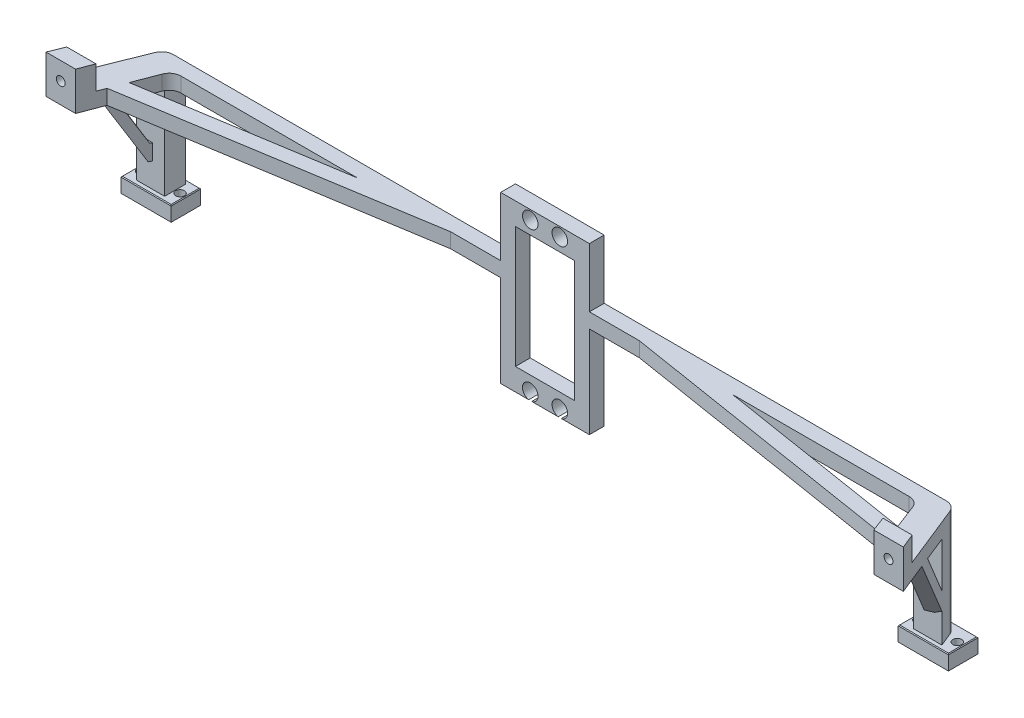
SolidWorks part; units mm, degrees
ref_plane "Plan de face" through (0, 0, 0) normal (0, 0, 1) x (1, 0, 0)
ref_plane "Plan de dessus" through (0, 0, 0) normal (0, 1, 0) x (1, 0, 0)
ref_plane "Plan de droite" through (0, 0, 0) normal (1, 0, 0) x (0, 0, -1)
sketch "Esquisse1" plane through (0, 0, 0) normal (0, 0, 1) x (1, 0, 0)
  line L0 (-10, 20.5) -> (10, 20.5)
  line L1 (-15, 25.5) -> (15, 25.5)
  line L2 (-15, 25.5) -> (-15, -25.5)
  line L3 (-15, -25.5) -> (15, -25.5)
  line L4 (15, 25.5) -> (15, -25.5)
  line L5 (-15, 25.5) -> (15, -25.5) construction
  line L6 (-15, -25.5) -> (15, 25.5) construction
  line L7 (10, 20.5) -> (10, -20.5)
  line L8 (-10, -20.5) -> (10, -20.5)
  line L9 (-10, 20.5) -> (-10, -20.5)
  point P0 (0, 0)
  dimension "D1" = 30
  dimension "D2" = 51
  dimension "D3" = 5
extrude "Boss.-Extru.1" add sketch "Esquisse1" along normal blind 5
ref_plane "Plan1" through (0, -3, 0) normal (0, -1, 0) x (-1, 0, 0)
sketch "Esquisse2" plane through (0, -3, 0) normal (0, -1, 0) x (-1, 0, 0)
  line L0 (-15, 0) -> (-130.7112, 0)
  line L1 (-140, 2.2361) -> (-140, -51.5937) construction
  line L2 (-125.9217, -2.5) -> (74.7377, -2.5) construction
  line L3 (-145, -28.8) -> (-135, -28.8)
  line L4 (-150.5755, -28.8) -> (-133, -28.8) construction
  line L5 (-134.4221, -2.5071) -> (-145, -28.8)
  line L6 (-15, -5) -> (-123.1664, -5)
  line L7 (-126.9037, -7.5744) -> (-135, -28.8)
  line L8 (-15, 0) -> (-15, -5)
  line L9 (0, 30.1998) -> (0, -12.5) construction
  line L10 (15, 0) -> (130.7112, 0)
  line L11 (134.4221, -2.5071) -> (145, -28.8)
  line L12 (145, -28.8) -> (135, -28.8)
  line L13 (126.9037, -7.5744) -> (135, -28.8)
  line L14 (15, -5) -> (123.1664, -5)
  line L15 (15, 0) -> (15, -5)
  arc A0 (-123.1664, -5) -> (-126.9037, -7.5744) centre (-123.1664, -9) ccw
  arc A1 (-130.7112, 0) -> (-134.4221, -2.5071) centre (-130.7112, -4) ccw
  arc A2 (130.7112, 0) -> (134.4221, -2.5071) centre (130.7112, -4) cw
  arc A3 (123.1664, -5) -> (126.9037, -7.5744) centre (123.1664, -9) cw
  point P12 (-140, -28.8)
  dimension "D2" = 4
  dimension "D1" = 10
ref_plane "Plan2" through (0, 8, 0) normal (0, 1, 0) x (1, 0, 0)
sketch "Esquisse3" plane through (0, 8, 0) normal (0, 1, 0) x (1, 0, 0)
  line L6 (130.7112, 0) -> (15, 0)
  line L7 (15, 0) -> (15, -5)
  line L8 (15, -5) -> (123.1664, -5)
  line L9 (126.9037, -7.5744) -> (135, -28.8)
  line L10 (135, -28.8) -> (145, -28.8)
  line L11 (145, -28.8) -> (134.4221, -2.5071)
  line L12 (130.7112, 0) -> (15, 0)
  line L13 (15, 0) -> (15, -5)
  line L14 (15, -5) -> (123.1664, -5)
  line L15 (126.9037, -7.5744) -> (135, -28.8)
  line L16 (135, -28.8) -> (145, -28.8)
  line L17 (145, -28.8) -> (134.4221, -2.5071)
  line L18 (-123.1664, -5) -> (-15, -5)
  line L19 (-135, -28.8) -> (-126.9037, -7.5744)
  line L20 (-145, -28.8) -> (-135, -28.8)
  line L21 (-134.4221, -2.5071) -> (-145, -28.8)
  line L22 (-15, 0) -> (-130.7112, 0)
  line L23 (-15, -5) -> (-15, 0)
  line L24 (-123.1664, -5) -> (-15, -5)
  line L25 (-135, -28.8) -> (-126.9037, -7.5744)
  line L26 (-145, -28.8) -> (-135, -28.8)
  line L27 (-134.4221, -2.5071) -> (-145, -28.8)
  line L28 (-15, 0) -> (-130.7112, 0)
  line L29 (-15, -5) -> (-15, 0)
  arc A2 (126.9037, -7.5744) -> (123.1664, -5) centre (123.1664, -9) ccw
  arc A3 (134.4221, -2.5071) -> (130.7112, 0) centre (130.7112, -4) ccw
  arc A4 (126.9037, -7.5744) -> (123.1664, -5) centre (123.1664, -9) ccw
  arc A5 (134.4221, -2.5071) -> (130.7112, 0) centre (130.7112, -4) ccw
  arc A6 (-123.1664, -5) -> (-126.9037, -7.5744) centre (-123.1664, -9) ccw
  arc A7 (-130.7112, 0) -> (-134.4221, -2.5071) centre (-130.7112, -4) ccw
  arc A8 (-123.1664, -5) -> (-126.9037, -7.5744) centre (-123.1664, -9) ccw
  arc A9 (-130.7112, 0) -> (-134.4221, -2.5071) centre (-130.7112, -4) ccw
  dimension "D1" = 0
  dimension "D2" = 0
extrude "Boss.-Extru.3" add sketch "Esquisse3" against normal blind 5
sketch "Esquisse4" plane through (0, 8, 0) normal (0, 1, 0) x (-1, 0, 0)
  line L0 (145, 28.8) -> (135, 28.8) construction
  line L1 (145, 28.8) -> (135, 28.8)
  line L2 (134.4221, 2.5071) -> (145, 28.8) construction
  line L3 (142.9885, 23.8) -> (145, 28.8)
  line L4 (135, 28.8) -> (126.9037, 7.5744) construction
  line L5 (135, 28.8) -> (133.0928, 23.8)
  line L6 (142.9885, 23.8) -> (133.0928, 23.8)
  line L7 (0, 89.6552) -> (0, -79.8852) construction
  line L8 (-142.9885, 23.8) -> (-145, 28.8)
  line L9 (-142.9885, 23.8) -> (-133.0928, 23.8)
  line L10 (-135, 28.8) -> (-133.0928, 23.8)
  line L11 (-145, 28.8) -> (-135, 28.8)
  dimension "D1" = 5
extrude "Boss.-Extru.4" add sketch "Esquisse4" along normal blind 8
sketch "Esquisse5" plane through (0, 25.5, 0) normal (0, 1, 0) x (1, 0, 0)
  line L4 (15, 0) -> (-15, 0)
  line L5 (-15, 0) -> (-15, -5)
  line L6 (-15, -5) -> (15, -5)
  line L7 (15, -5) -> (15, 0)
  line L8 (15, 0) -> (-15, 0)
  line L9 (-15, 0) -> (-15, -5)
  line L10 (-15, -5) -> (15, -5)
  line L11 (15, -5) -> (15, 0)
  dimension "D1" = 0
extrude "Boss.-Extru.5" add sketch "Esquisse5" along normal blind 2.5
sketch "Esquisse6" plane through (0, -25.5, 0) normal (0, -1, 0) x (1, 0, 0)
  line L4 (-15, 0) -> (15, 0)
  line L5 (15, 0) -> (15, 5)
  line L6 (15, 5) -> (-15, 5)
  line L7 (-15, 5) -> (-15, 0)
  line L8 (-15, 0) -> (15, 0)
  line L9 (15, 0) -> (15, 5)
  line L10 (15, 5) -> (-15, 5)
  line L11 (-15, 5) -> (-15, 0)
  dimension "D1" = 0
extrude "Boss.-Extru.6" add sketch "Esquisse6" along normal blind 2.5
sketch "Esquisse7" plane through (0, 0, 23.8) normal (0, 0, -1) x (-1, 0, 0)
  line L0 (0, 0) -> (0, 76.3627) construction
  circle A0 centre (-140, 10) radius 1.5
  circle A1 centre (140, 10) radius 1.5
extrude "Enlèv. mat.-Extru.1" cut sketch "Esquisse7" against normal through all
sketch "Esquisse8" plane through (0, 0, 5) normal (0, 0, 1) x (1, 0, 0)
  circle A0 centre (-5, 24.925) radius 2.625
  circle A1 centre (5, 24.925) radius 2.625
  circle A2 centre (-5, -25.425) radius 2.625
  circle A3 centre (5, -25.425) radius 2.625
extrude "Enlèv. mat.-Extru.2" cut sketch "Esquisse8" against normal through all
sketch "Esquisse10" plane through (15, 0, 0) normal (1, 0, 0) x (0, 0, -1)
  line L1 (-2.5, 33.5364) -> (-2.5, -60.476) construction
  line L2 (-5.5, -23) -> (0.5, -23)
  line L3 (-7.5, -25) -> (-7.5, -26)
  line L4 (0, -28) -> (0, 3)
  line L5 (0, 3) -> (-5, 3)
  line L6 (-5, 3) -> (-5, -28)
  line L7 (-5, -28) -> (0, -28)
  line L9 (0, 3) -> (-5, 3)
  line L12 (-5.5, -28) -> (0.5, -28)
  line L13 (2.5, -25) -> (2.5, -26)
  line L14 (-7.5, -23) -> (2.5, -28) construction
  line L15 (-7.5, -28) -> (2.5, -23) construction
  line L16 (-5, 28) -> (0, 28) construction
  line L17 (-5, 28) -> (0, 28)
  line L18 (0, -28) -> (-5, -28) construction
  arc A0 (0.5, -28) -> (2.5, -26) centre (0.5, -26) ccw
  arc A1 (0.5, -23) -> (2.5, -25) centre (0.5, -25) cw
  arc A2 (-7.5, -26) -> (-5.5, -28) centre (-5.5, -26) ccw
  arc A3 (-5.5, -23) -> (-7.5, -25) centre (-5.5, -25) ccw
  point P2 (-2.5, -25.5)
  point P11 (-2.5, -28)
  point P14 (-2.5, 28)
  dimension "D4" = 2
  dimension "D2" = 10
  dimension "D3" = 5
  dimension "D1" = 0
sketch "Esquisse12" plane through (0, 8, 0) normal (0, 1, 0) x (1, 0, 0)
  line L0 (-129.9983, -15.6872) -> (-63.4333, -5)
  line L1 (-133.0928, -23.8) -> (-126.9037, -7.5744) construction
  line L2 (-123.1664, -5) -> (-15, -5) construction
  line L3 (-132.0559, -21.0816) -> (-31.8922, -5)
  line L4 (-132.0559, -21.0816) -> (-129.9983, -15.6872)
  line L5 (-63.4333, -5) -> (-31.8922, -5)
  line L6 (0, 40.2666) -> (0, -55.5765) construction
  line L7 (132.0559, -21.0816) -> (129.9983, -15.6872)
  line L8 (132.0559, -21.0816) -> (31.8922, -5)
  line L9 (63.4333, -5) -> (31.8922, -5)
  line L10 (129.9983, -15.6872) -> (63.4333, -5)
  dimension "D1" = 60
  dimension "D2" = 5
extrude "Boss.-Extru.8" add sketch "Esquisse12" against normal blind 5
sketch "Esquisse13" plane through (0, 3, 0) normal (0, -1, 0) x (1, 0, 0)
  line L0 (-136.2297, 7) -> (-126.6846, 7)
  line L1 (-129.9983, 15.6872) -> (-126.9037, 7.5744) construction
  line L2 (-126.6846, 7) -> (-126.6846, 0)
  line L3 (0, 48.0822) -> (0, -50.1932) construction
  line L4 (136.2297, 7) -> (126.6846, 7)
  line L5 (126.6846, 7) -> (126.6846, 0)
  line L6 (130.7112, 0) -> (126.6846, 0)
  line L7 (-31.8922, 5) -> (-132.0559, 21.0816)
  line L8 (-132.0559, 21.0816) -> (-135, 28.8)
  line L9 (-135, 28.8) -> (-145, 28.8)
  line L10 (-145, 28.8) -> (-134.4221, 2.5071)
  line L11 (-130.7112, 0) -> (-15, 0)
  line L12 (-15, 0) -> (-15, 5)
  line L13 (-15, 5) -> (-31.8922, 5)
  line L14 (-31.8922, 5) -> (-132.0559, 21.0816)
  line L15 (-132.0559, 21.0816) -> (-135, 28.8)
  line L16 (-135, 28.8) -> (-145, 28.8)
  line L17 (-136.2297, 7) -> (-134.4221, 2.5071)
  line L18 (-130.7112, 0) -> (-126.6846, 0)
  line L19 (-15, 0) -> (-15, 5)
  line L20 (-15, 5) -> (-31.8922, 5)
  line L21 (132.0559, 21.0816) -> (31.8922, 5)
  line L22 (31.8922, 5) -> (15, 5)
  line L23 (15, 5) -> (15, 0)
  line L24 (15, 0) -> (130.7112, 0)
  line L25 (134.4221, 2.5071) -> (145, 28.8)
  line L26 (145, 28.8) -> (135, 28.8)
  line L27 (135, 28.8) -> (132.0559, 21.0816)
  line L29 (31.8922, 5) -> (15, 5)
  line L30 (15, 5) -> (15, 0)
  line L31 (126.6846, 0) -> (130.7112, 0)
  line L32 (134.4221, 2.5071) -> (136.2297, 7)
  line L34 (135, 28.8) -> (132.0559, 21.0816)
  line L35 (136.2297, 7) -> (134.4221, 2.5071)
  arc A0 (134.4221, 2.5071) -> (130.7112, 0) centre (130.7112, 4) cw
  arc A1 (-134.4221, 2.5071) -> (-130.7112, 0) centre (-130.7112, 4) ccw
  arc A2 (-134.4221, 2.5071) -> (-130.7112, 0) centre (-130.7112, 4) ccw
  arc A3 (130.7112, 0) -> (134.4221, 2.5071) centre (130.7112, 4) ccw
  arc A4 (130.7112, 0) -> (134.4221, 2.5071) centre (130.7112, 4) ccw
  line M20 (-145, 28.8) -> (-134.4221, 2.5071)
  arc M21 (-134.4221, 2.5071) -> (-130.7112, 0) centre (-130.7112, 4) ccw
  line M22 (-130.7112, 0) -> (-15, 0)
  dimension "D3" = 7
  dimension "D1" = 0
  dimension "D2" = 0
extrude "Boss.-Extru.9" add sketch "Esquisse13" along normal through all contours L2 L0 M20 M21 M22 | A0 L32 L4 L5 L6
sketch "Esquisse15" plane through (-114.8284, 0, -46.1964) normal (-0.9277, 0, -0.3732) x (-0.3732, 0, 0.9277)
  line L0 (56.0426, -14.3205) -> (66.0426, 3)
  line L1 (56.4099, -19.6843) -> (69.5067, 3)
  line L2 (56.0426, -14.3205) -> (56.4099, -19.6843)
  line L8 (75.4485, 8) -> (52.497, 8)
  line L9 (52.497, 8) -> (52.497, -28)
  line L10 (52.497, -28) -> (57.3399, -28)
  line L11 (57.3399, -28) -> (57.3399, 3)
  line L12 (57.3399, 3) -> (80.838, 3)
  line L13 (80.838, 3) -> (80.838, 16)
  line L14 (80.838, 16) -> (75.4485, 16)
  line L15 (75.4485, 16) -> (75.4485, 8)
  line L20 (66.0426, 3) -> (69.5067, 3)
  dimension "D2" = 60
  dimension "D3" = 20
  dimension "D4" = 3
  dimension "D1" = 0
extrude "Boss.-Extru.11" add sketch "Esquisse15" against normal blind 5
mirror "Symétrie3" about plane through (0, 0, 0) normal (1, 0, 0) of "Boss.-Extru.11"
sketch "Esquisse16" plane through (0, -28, 0) normal (0, -1, 0) x (1, 0, 0)
  line L0 (136.2297, 7) -> (126.6846, 7) construction
  line L1 (122.9572, 8.5) -> (139.9572, 8.5)
  line L2 (122.9572, 8.5) -> (122.9572, -1.5)
  line L3 (122.9572, -1.5) -> (139.9572, -1.5)
  line L4 (139.9572, 8.5) -> (139.9572, -1.5)
  line L5 (122.9572, 8.5) -> (139.9572, -1.5) construction
  line L6 (122.9572, -1.5) -> (139.9572, 8.5) construction
  line L7 (126.6846, 7) -> (126.6846, 0) construction
  line L8 (0, 67.4594) -> (0, -56.7864) construction
  line L9 (-122.9572, -1.5) -> (-139.9572, -1.5)
  line L10 (-139.9572, 8.5) -> (-139.9572, -1.5)
  line L11 (-122.9572, 8.5) -> (-139.9572, 8.5)
  line L12 (-122.9572, 8.5) -> (-122.9572, -1.5)
  line L13 (131.4572, 12.4366) -> (131.4572, -4.9018) construction
  circle A0 centre (124.9572, 3.5) radius 1.5
  circle A1 centre (137.9572, 3.5) radius 1.5
  circle A2 centre (-137.9572, 3.5) radius 1.5
  circle A3 centre (-124.9572, 3.5) radius 1.5
  point P0 (131.4572, 3.5)
  point P8 (131.4572, 7)
  point P11 (126.6846, 3.5)
  dimension "D5" = 3
  dimension "D1" = 17
  dimension "D2" = 10
  dimension "D3" = 5
  dimension "D4" = 2
extrude "Boss.-Extru.12" add sketch "Esquisse16" along normal blind 5
chamfer "Chanfrein3" distance 0.25 angle 45 8 edges at (-122.9572, -28, 3.5) (-131.4572, -28, -1.5) (-131.4572, -28, 8.5) (-139.9572, -28, 3.5) (139.9572, -28, 3.5) (131.4572, -28, -1.5) (131.4572, -28, 8.5) (122.9572, -28, 3.5)
sketch "Esquisse17" plane through (-20.4551, 3.7534, 50.8444) normal (0.3724, -0.0683, -0.9256) x (-0.9281, -0.0274, -0.3714)
  line L4 (119.3733, -20.22) -> (122.0605, -20.1462)
  line L5 (122.0605, -20.1462) -> (121.0001, -14.797)
  line L6 (121.0001, -14.797) -> (119.2256, -14.8458)
  line L7 (119.2256, -14.8458) -> (119.3733, -20.22)
  line L8 (119.3733, -20.22) -> (122.0605, -20.1462)
  line L9 (122.0605, -20.1462) -> (121.0001, -14.797)
  line L10 (121.0001, -14.797) -> (119.2256, -14.8458)
  line L11 (119.2256, -14.8458) -> (119.3733, -20.22)
  dimension "D1" = 0
extrude "Boss.-Extru.13" add sketch "Esquisse17" along normal blind 5
sketch "Esquisse18" plane through (20.4551, 3.7534, 50.8444) normal (-0.3724, -0.0683, -0.9256) x (-0.9281, 0.0274, 0.3714)
  line L4 (-119.2256, -14.8458) -> (-121.0001, -14.797)
  line L5 (-121.0001, -14.797) -> (-122.0605, -20.1462)
  line L6 (-122.0605, -20.1462) -> (-119.3733, -20.22)
  line L7 (-119.3733, -20.22) -> (-119.2256, -14.8458)
  line L8 (-119.2256, -14.8458) -> (-121.0001, -14.797)
  line L9 (-121.0001, -14.797) -> (-122.0605, -20.1462)
  line L10 (-122.0605, -20.1462) -> (-119.3733, -20.22)
  line L11 (-119.3733, -20.22) -> (-119.2256, -14.8458)
  dimension "D1" = 0
extrude "Boss.-Extru.14" add sketch "Esquisse18" along normal blind 5
